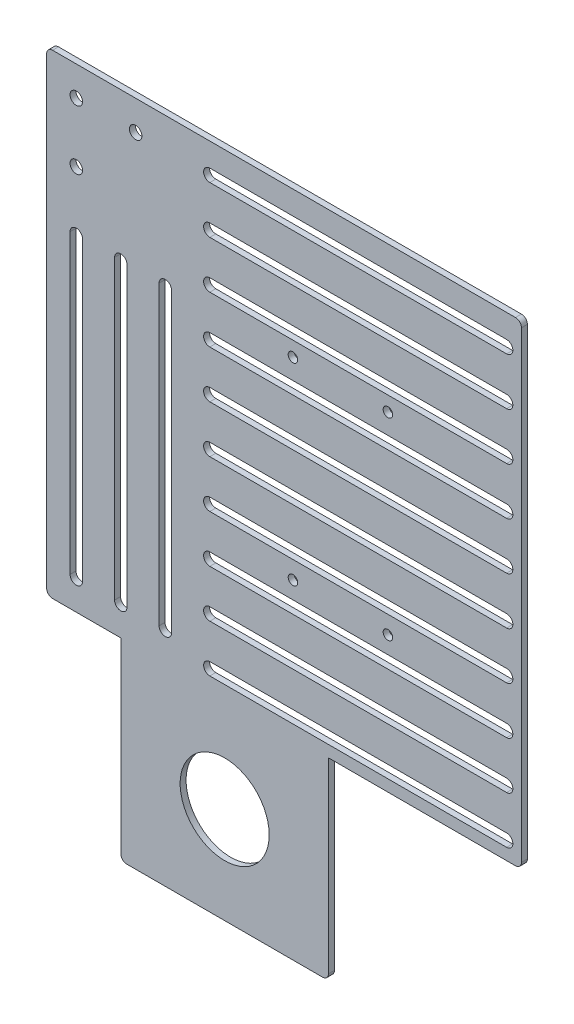
SolidWorks part; units mm, degrees
ref_plane "前视基准面" through (0, 0, 0) normal (0, 0, 1) x (1, 0, 0)
ref_plane "上视基准面" through (0, 0, 0) normal (0, 1, 0) x (1, 0, 0)
ref_plane "右视基准面" through (0, 0, 0) normal (1, 0, 0) x (0, 0, -1)
sketch "草图1" plane through (0, 0, 0) normal (0, 0, 1) x (1, 0, 0)
  line L1 (-80, 80) -> (80, 80)
  line L2 (-80, 80) -> (-80, -80)
  line L3 (-80, -80) -> (80, -80)
  line L4 (80, 80) -> (80, -80)
  line L5 (-80, 80) -> (80, -80) construction
  line L6 (-80, -80) -> (80, 80) construction
  point P0 (0, 0)
  dimension "D1" = 160
  dimension "D2" = 160
extrude "凸台-拉伸1" add sketch "草图1" along normal blind 2
sketch "草图2" plane through (0, 0, 2) normal (0, 0, 1) x (1, 0, 0)
  line L0 (-55, -80) -> (-55, -145)
  line L1 (-80, -80) -> (80, -80) construction
  line L2 (-55, -145) -> (15, -145)
  line L3 (15, -145) -> (15, -80)
  line L4 (-80, 80) -> (-80, -80) construction
  line L5 (-55, -80) -> (15, -80)
  dimension "D1" = 25
  dimension "D2" = 70
  dimension "D3" = 65
extrude "凸台-拉伸2" add sketch "草图2" against normal through all
sketch "草图3" plane through (0, 0, 2) normal (0, 0, 1) x (1, 0, 0)
  line L0 (-80, 80) -> (-80, -80) construction
  line L1 (-80, 80) -> (80, 80) construction
  circle A0 centre (-70, 70) radius 2.1
  circle A1 centre (-50, 70) radius 2.1
  circle A3 centre (-70, 50) radius 2.1
  circle A4 centre (-50, 50) radius 2.1 [skipped]
  dimension "D1" = 10
  dimension "D3" = 4.2
  dimension "D2" = 10
  dimension "D6" = 20
  dimension "D7" = 20
  dimension "D4" = 2
  dimension "D5" = 2
extrude "切除-拉伸1" cut sketch "草图3" against normal through all
sketch "草图4" plane through (0, 0, 2) normal (0, 0, 1) x (1, 0, 0)
  line L0 (-25, 70) -> (75, 70) construction
  line L1 (-25, 72.1) -> (75, 72.1)
  line L2 (-25, 67.9) -> (75, 67.9)
  line L3 (80, 80) -> (80, -80) construction
  line L4 (-55, -145) -> (15, -80) construction
  line L5 (-80, 80) -> (80, 80) construction
  line L6 (-70, 30) -> (-70, -70) construction
  line L7 (-67.9, 30) -> (-67.9, -70)
  line L8 (-72.1, 30) -> (-72.1, -70)
  line L9 (-55, -80) -> (-55, -145) construction
  line L10 (-80, -80) -> (80, -80) construction
  line L11 (-25, 54) -> (75, 54) construction
  line L12 (-25, 56.1) -> (75, 56.1)
  line L13 (-25, 51.9) -> (75, 51.9)
  line L14 (-25, 38) -> (75, 38) construction
  line L15 (-25, 40.1) -> (75, 40.1)
  line L16 (-25, 35.9) -> (75, 35.9)
  line L17 (-25, 22) -> (75, 22) construction
  line L18 (-25, 24.1) -> (75, 24.1)
  line L19 (-25, 19.9) -> (75, 19.9)
  line L20 (-25, 6) -> (75, 6) construction
  line L21 (-25, 8.1) -> (75, 8.1)
  line L22 (-25, 3.9) -> (75, 3.9)
  line L23 (-25, -10) -> (75, -10) construction
  line L24 (-25, -7.9) -> (75, -7.9)
  line L25 (-25, -12.1) -> (75, -12.1)
  line L26 (-25, -26) -> (75, -26) construction
  line L27 (-25, -23.9) -> (75, -23.9)
  line L28 (-25, -28.1) -> (75, -28.1)
  line L29 (-25, -42) -> (75, -42) construction
  line L30 (-25, -39.9) -> (75, -39.9)
  line L31 (-25, -44.1) -> (75, -44.1)
  line L32 (-25, -58) -> (75, -58) construction
  line L33 (-25, -55.9) -> (75, -55.9)
  line L34 (-25, -60.1) -> (75, -60.1)
  line L35 (-25, -74) -> (75, -74) construction
  line L36 (-25, -71.9) -> (75, -71.9)
  line L37 (-25, -76.1) -> (75, -76.1)
  line L38 (-57.1, 30) -> (-57.1, -70)
  line L39 (-52.9, 30) -> (-52.9, -70)
  line L40 (-55, 30) -> (-55, -70) construction
  line L41 (-42.1, 30) -> (-42.1, -70)
  line L42 (-37.9, 30) -> (-37.9, -70)
  line L43 (-40, 30) -> (-40, -70) construction
  line L44 (-55, -145) -> (15, -145) construction
  arc A0 (-25, 72.1) -> (-25, 67.9) centre (-25, 70) ccw
  arc A1 (75, 67.9) -> (75, 72.1) centre (75, 70) ccw
  arc A2 (-67.9, 30) -> (-72.1, 30) centre (-70, 30) ccw
  arc A3 (-72.1, -70) -> (-67.9, -70) centre (-70, -70) ccw
  arc A4 (-25, 56.1) -> (-25, 51.9) centre (-25, 54) ccw
  arc A5 (75, 51.9) -> (75, 56.1) centre (75, 54) ccw
  arc A6 (-25, 40.1) -> (-25, 35.9) centre (-25, 38) ccw
  arc A7 (75, 35.9) -> (75, 40.1) centre (75, 38) ccw
  arc A8 (-25, 24.1) -> (-25, 19.9) centre (-25, 22) ccw
  arc A9 (75, 19.9) -> (75, 24.1) centre (75, 22) ccw
  arc A10 (-25, 8.1) -> (-25, 3.9) centre (-25, 6) ccw
  arc A11 (75, 3.9) -> (75, 8.1) centre (75, 6) ccw
  arc A12 (-25, -7.9) -> (-25, -12.1) centre (-25, -10) ccw
  arc A13 (75, -12.1) -> (75, -7.9) centre (75, -10) ccw
  arc A14 (-25, -23.9) -> (-25, -28.1) centre (-25, -26) ccw
  arc A15 (75, -28.1) -> (75, -23.9) centre (75, -26) ccw
  arc A16 (-25, -39.9) -> (-25, -44.1) centre (-25, -42) ccw
  arc A17 (75, -44.1) -> (75, -39.9) centre (75, -42) ccw
  arc A18 (-25, -55.9) -> (-25, -60.1) centre (-25, -58) ccw
  arc A19 (75, -60.1) -> (75, -55.9) centre (75, -58) ccw
  arc A20 (-25, -71.9) -> (-25, -76.1) centre (-25, -74) ccw
  arc A21 (75, -76.1) -> (75, -71.9) centre (75, -74) ccw
  arc A22 (-52.9, 30) -> (-57.1, 30) centre (-55, 30) ccw
  arc A23 (-57.1, -70) -> (-52.9, -70) centre (-55, -70) ccw
  arc A24 (-37.9, 30) -> (-42.1, 30) centre (-40, 30) ccw
  arc A25 (-42.1, -70) -> (-37.9, -70) centre (-40, -70) ccw
  circle A26 centre (-20, -112.5) radius 15
  point P2 (25, 70)
  point P14 (-70, -20)
  point P24 (25, 54)
  point P31 (25, 38)
  point P38 (25, 22)
  point P45 (25, 6)
  point P52 (25, -10)
  point P59 (25, -26)
  point P66 (25, -42)
  point P73 (25, -58)
  point P80 (25, -74)
  point P88 (-55, -20)
  point P95 (-40, -20)
  dimension "D1" = 2.1
  dimension "D6" = 2.1
  dimension "D12" = 30
  dimension "D2" = 5
  dimension "D3" = 100
  dimension "D4" = 10
  dimension "D5" = 10
  dimension "D7" = 100
  dimension "D9" = 16
  dimension "D11" = 15
  dimension "D8" = 10
  dimension "D10" = 3
extrude "切除-拉伸2" cut sketch "草图4" against normal blind 10
fillet "圆角1" radius 2 6 edges at (-55, -145, 1) (15, -145, 1) (80, -80, 1) (-80, -80, 1) (-80, 80, 1) (80, 80, 1)
sketch "草图5" plane through (0, 0, 2) normal (0, 0, 1) x (1, 0, 0)
  line L0 (80, 80) -> (80, -80) construction
  line L1 (3, 30.9) -> (35, 30.9) construction
  line L2 (3, 30.9) -> (3, -34.1) construction
  line L3 (3, -34.1) -> (35, -34.1) construction
  line L4 (35, 30.9) -> (35, -34.1) construction
  line L5 (-25, 35.9) -> (75, 35.9) construction
  circle A0 centre (35, 30.9) radius 1.6
  circle A1 centre (3, 30.9) radius 1.6
  circle A2 centre (3, -34.1) radius 1.6
  circle A3 centre (35, -34.1) radius 1.6
  point P4 (0, 0)
  dimension "D3" = 45
  dimension "D5" = 3.2
  dimension "D8" = 65
  dimension "D9" = 32
  dimension "D1" = 32
  dimension "D4" = 5
  dimension "D6" = 2
  dimension "D7" = 2
extrude "切除-拉伸3" cut sketch "草图5" against normal blind 10
